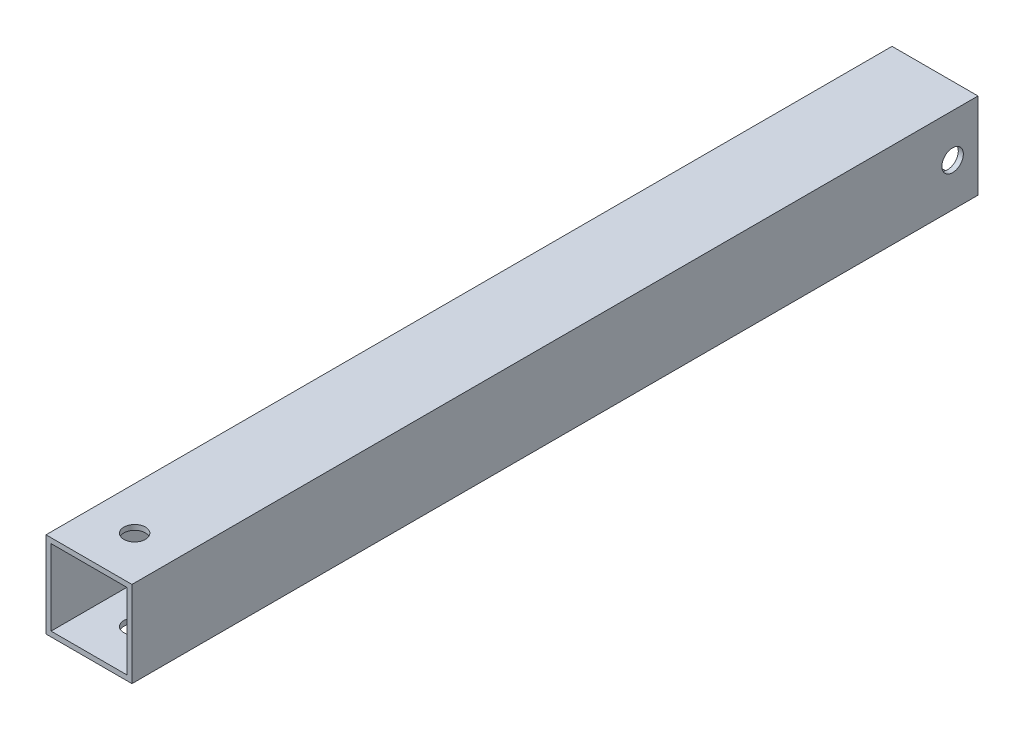
SolidWorks part; units mm, degrees
material "AISI 1020 Acero laminado en frío"
ref_plane "Alzado" through (0, 0, 0) normal (0, 0, 1) x (1, 0, 0)
ref_plane "Planta" through (0, 0, 0) normal (0, 1, 0) x (1, 0, 0)
ref_plane "Vista lateral" through (0, 0, 0) normal (1, 0, 0) x (0, 0, -1)
sketch "Croquis1" plane through (0, 0, 0) normal (0, 0, 1) x (1, 0, 0)
  line L0 (-22.4, 22.4) -> (22.4, 22.4)
  line L1 (-25.4, -25.4) -> (25.4, -25.4)
  line L2 (-25.4, -25.4) -> (-25.4, 25.4)
  line L3 (-25.4, 25.4) -> (25.4, 25.4)
  line L4 (25.4, -25.4) -> (25.4, 25.4)
  line L5 (-25.4, -25.4) -> (25.4, 25.4) construction
  line L6 (-25.4, 25.4) -> (25.4, -25.4) construction
  line L7 (22.4, -22.4) -> (22.4, 22.4)
  line L8 (-22.4, -22.4) -> (22.4, -22.4)
  line L9 (-22.4, -22.4) -> (-22.4, 22.4)
  point P0 (0, 0)
  dimension "D1" = 50.8
  dimension "D2" = 50.8
  dimension "D3" = 3
extrude "Saliente-Extruir1" add sketch "Croquis1" along normal mid plane 500
sketch "Croquis2" plane through (25.4, 0, 0) normal (1, 0, 0) x (0, 0, -1)
  line L0 (-250, 0) -> (250, 0) construction
  line L1 (-250, -25.4) -> (-250, 25.4) construction
  line L2 (250, -25.4) -> (250, 25.4) construction
  line L3 (-250, -25.4) -> (250, -25.4) construction
  line L5 (-250, 25.4) -> (250, 25.4) construction
  line L6 (0, 25.4) -> (0, -25.4) construction
  circle A1 centre (235, 0) radius 6.35
  point P18 (-250, 0)
  dimension "D1" = 12.7
  dimension "D4" = 15
extrude "Cortar-Extruir1" cut sketch "Croquis2" against normal through all
sketch "Croquis3" plane through (0, 25.4, 0) normal (0, 1, 0) x (1, 0, 0)
  line L0 (44.2746, -223) -> (-44.1968, -223) construction
  line L1 (25.4, -250) -> (-25.4, -250) construction
  line L2 (0, -250) -> (0, -192.0651) construction
  circle A0 centre (0, -223) radius 6.35
  dimension "D1" = 12.7
  dimension "D2" = 27
extrude "Cortar-Extruir2" cut sketch "Croquis3" against normal blind 70
